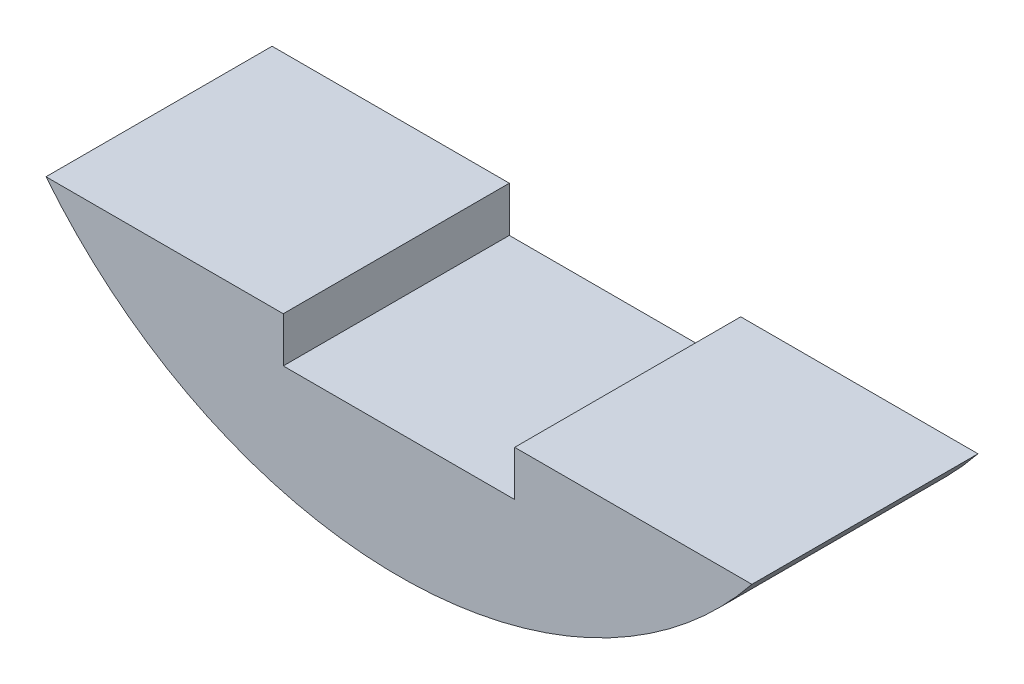
SolidWorks part; units mm, degrees
material "ABS"
ref_plane "Front Plane" through (0, 0, 0) normal (0, 0, 1) x (1, 0, 0)
ref_plane "Top Plane" through (0, 0, 0) normal (0, 1, 0) x (1, 0, 0)
ref_plane "Right Plane" through (0, 0, 0) normal (1, 0, 0) x (0, 0, -1)
sketch "Sketch1" plane through (0, 0, 0) normal (0, 0, 1) x (1, 0, 0)
  line L0 (0, 0) -> (79.3115, 0)
  arc A0 (0, 0) -> (79.3115, 0) centre (39.6557, 31.75) ccw
  dimension "D1" = 50.8
  dimension "D2" = 31.75
extrude "Boss-Extrude1" add sketch "Sketch1" along normal blind 25.4
sketch "Sketch4" plane through (0, 0, 0) normal (0, 1, 0) x (1, 0, 0)
  line L0 (79.3115, 0) -> (0, 0) construction
  line L1 (26.6557, 0) -> (52.6557, 0)
  line L2 (26.6557, 0) -> (26.6557, -25.4)
  line L3 (26.6557, -25.4) -> (52.6557, -25.4)
  line L4 (52.6557, 0) -> (52.6557, -25.4)
  line L5 (79.3115, -25.4) -> (0, -25.4) construction
  point P8 (39.6557, 0)
  point P9 (39.6557, -25.4)
  dimension "D1" = 26
extrude "Cut-Extrude3" cut sketch "Sketch4" against normal blind 5.08
